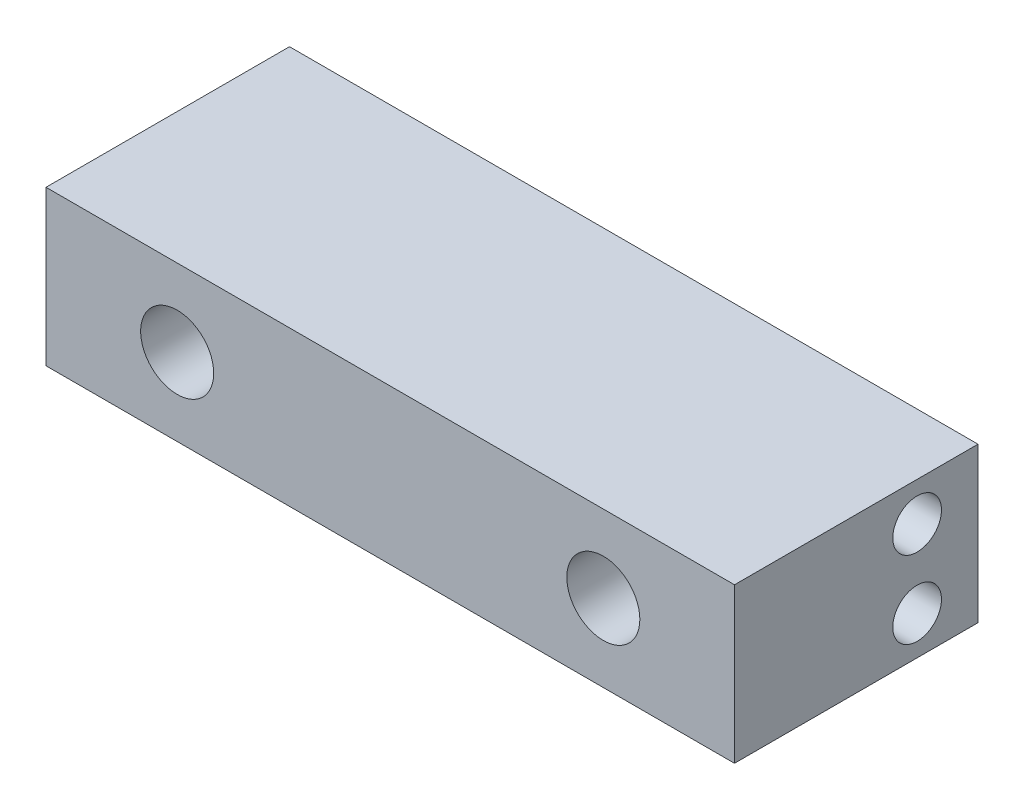
SolidWorks part; units mm, degrees
material "6061-T6 (SS)"
ref_plane "X-Y Datum" through (0, 0, 0) normal (0, 0, 1) x (1, 0, 0)
ref_plane "X-Z Datum" through (0, 0, 0) normal (0, 1, 0) x (1, 0, 0)
ref_plane "Y-Z Datum" through (0, 0, 0) normal (1, 0, 0) x (0, 0, -1)
sketch "Sketch1" plane through (0, 0, 0) normal (0, 0, 1) x (1, 0, 0)
  line L1 (-28.275, 6.35) -> (28.275, 6.35)
  line L2 (-28.275, 6.35) -> (-28.275, -6.35)
  line L3 (-28.275, -6.35) -> (28.275, -6.35)
  line L4 (28.275, 6.35) -> (28.275, -6.35)
  line L5 (-28.275, 6.35) -> (28.275, -6.35) construction
  line L6 (-28.275, -6.35) -> (28.275, 6.35) construction
  point P0 (0, 0)
  dimension "D1" = 56.55
  dimension "D2" = 12.7
extrude "Boss-Extrude1" add sketch "Sketch1" along normal blind 20 contours L2 L3 L4 L1
sketch "Sketch2" plane through (0, 0, 20) normal (0, 0, 1) x (1, 0, 0)
  line L0 (-28.275, 0) -> (28.275, 0) construction
  line L1 (-28.275, 6.35) -> (-28.275, -6.35) construction
  line L2 (28.275, 6.35) -> (28.275, -6.35) construction
  line L3 (-17.5, 0) -> (17.5, 0) construction
  circle A0 centre (17.5, 0) radius 3
  circle A1 centre (-17.5, 0) radius 3
  point P10 (0, 0)
  dimension "D1" = 6
  dimension "D2" = 35
extrude "Cut-Extrude1" cut sketch "Sketch2" against normal blind 12 contours A1 L0 L3 | L0 A1 L3 | L0 L3 A0 | L3 L0 A0
sketch "Sketch3" plane through (-28.275, 0, 0) normal (-1, 0, 0) x (0, 0, 1)
  line L0 (0, 0) -> (20, 0)
  line L1 (20, 6.35) -> (20, -6.35) construction
  line L2 (5, 3.175) -> (5, -3.175)
  circle A0 centre (5, 3.175) radius 2
  circle A1 centre (5, -3.175) radius 2
  point P8 (5, 0)
  dimension "D1" = 4
  dimension "D3" = 5
  dimension "D2" = 6.35
extrude "Cut-Extrude2" cut sketch "Sketch3" against normal blind 14
mirror "Mirror1" about plane through (0, 0, 0) normal (1, 0, 0) of "Cut-Extrude2"
